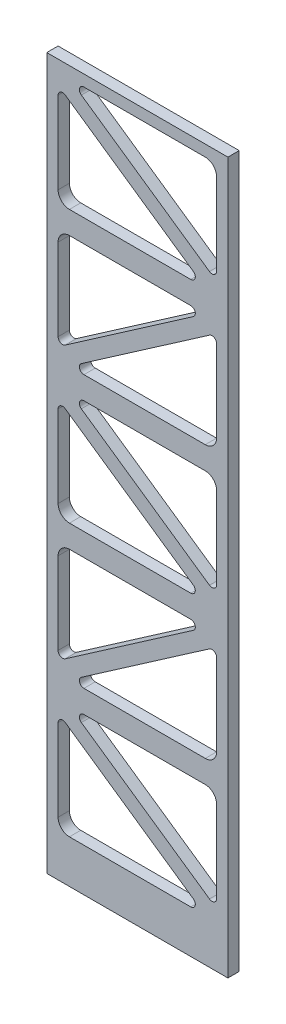
SolidWorks part; units mm, degrees
ref_plane "Front Plane" through (0, 0, 0) normal (0, 0, 1) x (1, 0, 0)
ref_plane "Top Plane" through (0, 0, 0) normal (0, 1, 0) x (1, 0, 0)
ref_plane "Right Plane" through (0, 0, 0) normal (1, 0, 0) x (0, 0, -1)
sketch "Model" plane through (0, 0, 0) normal (0, 0, 1) x (1, 0, 0)
  line L0 (88.9, 87.63) -> (20.8312, 87.63)
  line L1 (95.25, 35.3278) -> (95.25, 81.28)
  line L2 (19.3854, 83.0016) -> (91.2642, 33.2394)
  line L3 (6.35, 157.48) -> (6.35, 111.5278)
  line L4 (80.7688, 163.83) -> (12.7, 163.83)
  line L5 (10.3358, 109.4394) -> (82.2146, 159.2016)
  line L6 (88.9, 240.03) -> (20.8312, 240.03)
  line L7 (95.25, 187.7278) -> (95.25, 233.68)
  line L8 (19.3854, 235.4016) -> (91.2642, 185.6394)
  line L9 (12.7, 176.53) -> (80.7688, 176.53)
  line L10 (6.35, 228.8322) -> (6.35, 182.88)
  line L11 (82.2146, 181.1584) -> (10.3358, 230.9206)
  line L12 (91.2642, 154.7206) -> (19.3854, 104.9584)
  line L13 (95.25, 106.68) -> (95.25, 152.6322)
  line L14 (20.8312, 100.33) -> (88.9, 100.33)
  line L15 (6.35, 309.88) -> (6.35, 263.9278)
  line L16 (80.7688, 316.23) -> (12.7, 316.23)
  line L17 (10.3358, 261.8394) -> (82.2146, 311.6016)
  line L18 (88.9, 392.43) -> (20.8312, 392.43)
  line L19 (95.25, 340.1278) -> (95.25, 386.08)
  line L20 (19.3854, 387.8016) -> (91.2642, 338.0394)
  line L21 (12.7, 328.93) -> (80.7688, 328.93)
  line L22 (6.35, 381.2322) -> (6.35, 335.28)
  line L23 (82.2146, 333.5584) -> (10.3358, 383.3206)
  line L24 (12.7, 24.13) -> (80.7688, 24.13)
  line L25 (6.35, 76.4322) -> (6.35, 30.48)
  line L26 (82.2146, 28.7584) -> (10.3358, 78.5206)
  line L27 (91.2642, 307.1206) -> (19.3854, 257.3584)
  line L28 (95.25, 259.08) -> (95.25, 305.0322)
  line L29 (20.8312, 252.73) -> (88.9, 252.73)
  line L30 (0, 398.78) -> (0, 0)
  line L31 (0, 0) -> (101.6, 0)
  line L32 (101.6, 398.78) -> (101.6, 0)
  line L33 (0, 398.78) -> (101.6, 398.78)
  arc A0 (95.25, 81.28) -> (88.9, 87.63) centre (88.9, 81.28) ccw
  arc A1 (91.2642, 33.2394) -> (95.25, 35.3278) centre (92.71, 35.3278) ccw
  arc A2 (20.8312, 87.63) -> (19.3854, 83.0016) centre (20.8312, 85.09) ccw
  arc A3 (12.7, 163.83) -> (6.35, 157.48) centre (12.7, 157.48) ccw
  arc A4 (82.2146, 159.2016) -> (80.7688, 163.83) centre (80.7688, 161.29) ccw
  arc A5 (6.35, 111.5278) -> (10.3358, 109.4394) centre (8.89, 111.5278) ccw
  arc A6 (95.25, 233.68) -> (88.9, 240.03) centre (88.9, 233.68) ccw
  arc A7 (91.2642, 185.6394) -> (95.25, 187.7278) centre (92.71, 187.7278) ccw
  arc A8 (20.8312, 240.03) -> (19.3854, 235.4016) centre (20.8312, 237.49) ccw
  arc A9 (6.35, 182.88) -> (12.7, 176.53) centre (12.7, 182.88) ccw
  arc A10 (10.3358, 230.9206) -> (6.35, 228.8322) centre (8.89, 228.8322) ccw
  arc A11 (80.7688, 176.53) -> (82.2146, 181.1584) centre (80.7688, 179.07) ccw
  arc A12 (95.25, 152.6322) -> (91.2642, 154.7206) centre (92.71, 152.6322) ccw
  arc A13 (88.9, 100.33) -> (95.25, 106.68) centre (88.9, 106.68) ccw
  arc A14 (19.3854, 104.9584) -> (20.8312, 100.33) centre (20.8312, 102.87) ccw
  arc A15 (12.7, 316.23) -> (6.35, 309.88) centre (12.7, 309.88) ccw
  arc A16 (82.2146, 311.6016) -> (80.7688, 316.23) centre (80.7688, 313.69) ccw
  arc A17 (6.35, 263.9278) -> (10.3358, 261.8394) centre (8.89, 263.9278) ccw
  arc A18 (95.25, 386.08) -> (88.9, 392.43) centre (88.9, 386.08) ccw
  arc A19 (91.2642, 338.0394) -> (95.25, 340.1278) centre (92.71, 340.1278) ccw
  arc A20 (20.8312, 392.43) -> (19.3854, 387.8016) centre (20.8312, 389.89) ccw
  arc A21 (6.35, 335.28) -> (12.7, 328.93) centre (12.7, 335.28) ccw
  arc A22 (10.3358, 383.3206) -> (6.35, 381.2322) centre (8.89, 381.2322) ccw
  arc A23 (80.7688, 328.93) -> (82.2146, 333.5584) centre (80.7688, 331.47) ccw
  arc A24 (6.35, 30.48) -> (12.7, 24.13) centre (12.7, 30.48) ccw
  arc A25 (10.3358, 78.5206) -> (6.35, 76.4322) centre (8.89, 76.4322) ccw
  arc A26 (80.7688, 24.13) -> (82.2146, 28.7584) centre (80.7688, 26.67) ccw
  arc A27 (95.25, 305.0322) -> (91.2642, 307.1206) centre (92.71, 305.0322) ccw
  arc A28 (88.9, 252.73) -> (95.25, 259.08) centre (88.9, 259.08) ccw
  arc A29 (19.3854, 257.3584) -> (20.8312, 252.73) centre (20.8312, 255.27) ccw
extrude "Boss-Extrude1" add sketch "Model" along normal blind 6.35
equation "\"thick\"=0.25"
equation "\"D1@Boss-Extrude1\"=\"thick\""
